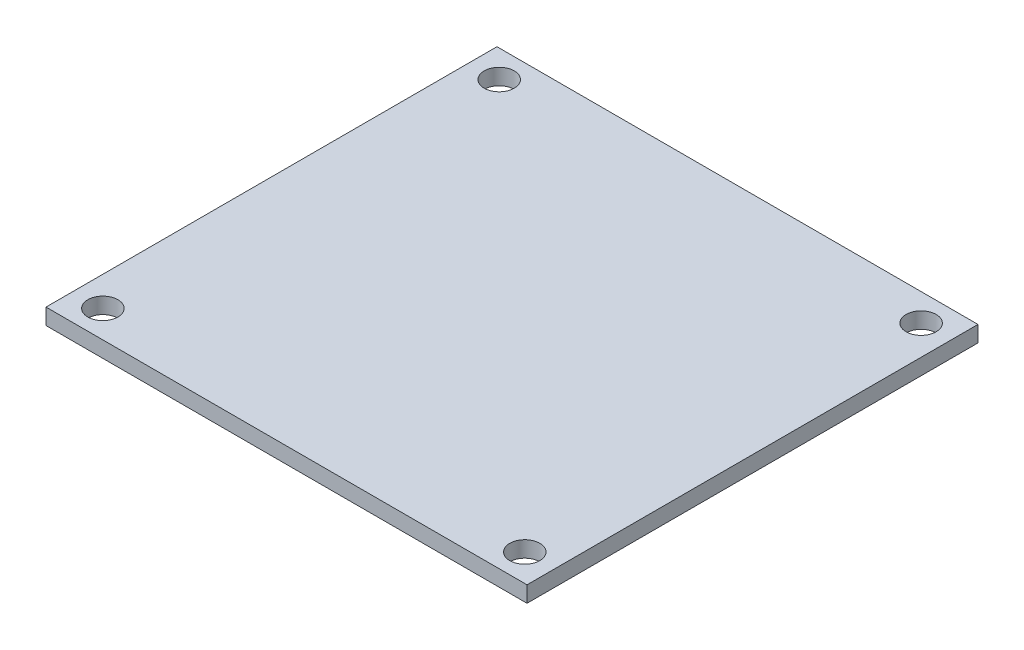
SolidWorks part; units mm, degrees
ref_plane "Alzado" through (0, 0, 0) normal (0, 0, 1) x (1, 0, 0)
ref_plane "Planta" through (0, 0, 0) normal (0, 1, 0) x (1, 0, 0)
ref_plane "Vista lateral" through (0, 0, 0) normal (1, 0, 0) x (0, 0, -1)
sketch "Croquis1" plane through (0, 0, 0) normal (0, 1, 0) x (1, 0, 0)
  line L1 (-24, -22.5) -> (24, -22.5)
  line L2 (-24, -22.5) -> (-24, 22.5)
  line L3 (-24, 22.5) -> (24, 22.5)
  line L4 (24, -22.5) -> (24, 22.5)
  line L5 (-24, -22.5) -> (24, 22.5) construction
  line L6 (-24, 22.5) -> (24, -22.5) construction
  line L7 (-21.05, -19.775) -> (21.05, -19.775) construction
  line L8 (-21.05, -19.775) -> (-21.05, 19.775) construction
  line L9 (-21.05, 19.775) -> (21.05, 19.775) construction
  line L10 (21.05, -19.775) -> (21.05, 19.775) construction
  line L11 (-21.05, -19.775) -> (21.05, 19.775) construction
  line L12 (-21.05, 19.775) -> (21.05, -19.775) construction
  circle A0 centre (21.05, 19.775) radius 1.5
  circle A1 centre (-21.05, 19.775) radius 1.5
  circle A2 centre (-21.05, -19.775) radius 1.5
  circle A3 centre (21.05, -19.775) radius 1.5
  point P0 (0, 0)
  point P6 (0, 0)
  dimension "D5" = 3
  dimension "D1" = 45
  dimension "D2" = 48
  dimension "D3" = 42.1
  dimension "D4" = 39.55
extrude "Saliente-Extruir1" add sketch "Croquis1" along normal blind 1.6
